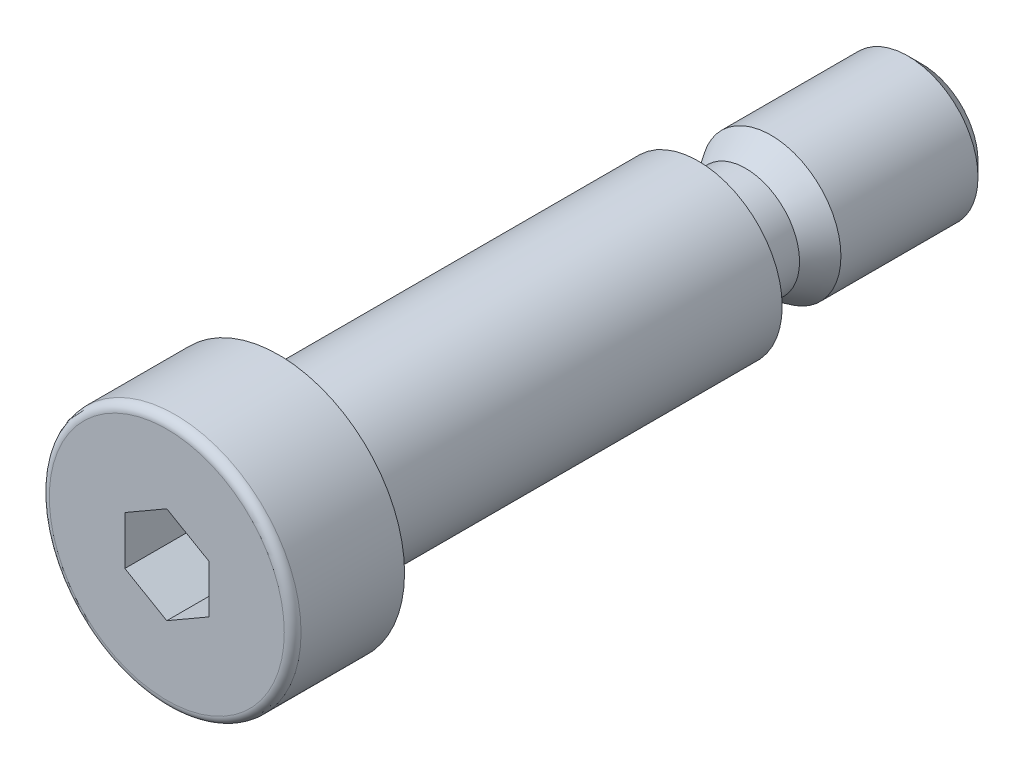
SolidWorks part; units mm, degrees
material "1.0545 (S355N)"
ref_plane "Płaszczyzna przednia" through (0, 0, 0) normal (0, 0, 1) x (1, 0, 0)
ref_plane "Płaszczyzna górna" through (0, 0, 0) normal (0, 1, 0) x (1, 0, 0)
ref_plane "Płaszczyzna prawa" through (0, 0, 0) normal (1, 0, 0) x (0, 0, -1)
sketch "Szkic1" plane through (0, 0, 0) normal (0, 1, 0) x (1, 0, 0)
  line L0 (5, 20.2) -> (3.85, 18.39)
  line L1 (9, -23) -> (-9, -23)
  line L2 (9, -23) -> (9, -15)
  line L3 (9, -15) -> (-9, -15)
  line L4 (-9, -23) -> (-9, -15)
  line L5 (6, -15) -> (-6, -15)
  line L6 (6, -15) -> (6, 15)
  line L7 (6, 15) -> (-6, 15)
  line L8 (-6, -15) -> (-6, 15)
  line L9 (-3.85, 15) -> (3.85, 15)
  line L10 (-3.85, 15) -> (-3.85, 18.39)
  line L11 (-3.85, 18.39) -> (3.85, 18.39)
  line L12 (3.85, 15) -> (3.85, 18.39)
  line L13 (5, 20.2) -> (5, 30)
  line L14 (5, 30) -> (4, 31)
  line L15 (4, 31) -> (-4, 31)
  line L16 (-4, 31) -> (-5, 30)
  line L17 (-5, 30) -> (-5, 20.2)
  line L18 (-5, 20.2) -> (-3.85, 18.39)
  line L19 (5, 20.2) -> (-5, 20.2) construction
  line L20 (5, 30) -> (-5, 30) construction
  line L21 (0, -19.9356) -> (0, 25.6583) construction
  line L22 (0, -23) -> (0, 31)
  point P4 (0, -15)
  point P14 (0, -15)
  point P15 (0, 15)
  point P16 (0, 15)
  point P17 (-6, 0)
  point P23 (0, 20.2)
  point P25 (0, 31)
  point P26 (0, 18.39)
  point P27 (0, 30)
  dimension "D1" = 18
  dimension "D2" = 8
  dimension "D3" = 12
  dimension "l1" = 30
  dimension "D5" = 7.7
  dimension "D6" = 16
  dimension "D7" = 10
  dimension "D8" = 8
  dimension "D9" = 1
  dimension "D10" = 1.81
  dimension "D11" = 9.8
revolve "Obrót1" add sketch "Szkic1" angle 360 about L22
sketch "Szkic2" plane through (0, 0, 23) normal (0, 0, 1) x (1, 0, 0)
  line L1 (3, 1.7321) -> (0, 3.4641)
  line L2 (0, 3.4641) -> (-3, 1.7321)
  line L3 (-3, 1.7321) -> (-3, -1.7321)
  line L4 (-3, -1.7321) -> (0, -3.4641)
  line L5 (0, -3.4641) -> (3, -1.7321)
  line L6 (3, -1.7321) -> (3, 1.7321)
  circle A0 centre (0, 0) radius 3 construction
  dimension "D1" = 6
extrude "Wytnij-wyciągnięcie1" cut sketch "Szkic2" against normal blind 4.9
fillet "Zaokrąglenie1" radius 0.6 1 edges at (9, 0, 23)
